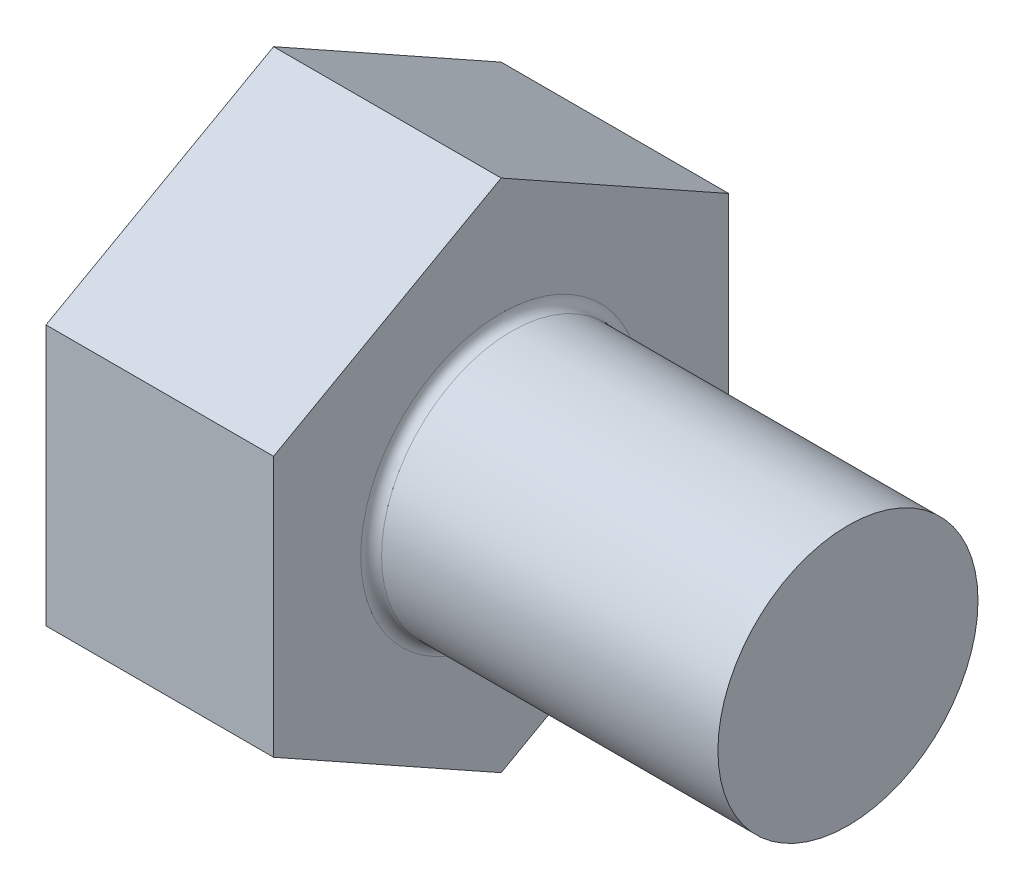
SolidWorks part; units mm, degrees
material "Brass"
ref_plane "Front Plane" through (0, 0, 0) normal (0, 0, 1) x (1, 0, 0)
ref_plane "Top Plane" through (0, 0, 0) normal (0, 1, 0) x (1, 0, 0)
ref_plane "Right Plane" through (0, 0, 0) normal (1, 0, 0) x (0, 0, -1)
sketch "Sketch1" plane through (0, 0, 0) normal (0, 0, 1) x (1, 0, 0)
  line L0 (-10.5833, 0) -> (15.2015, 0) construction
  line L2 (0, 0) -> (8.4667, 0)
  line L3 (0, 0) -> (0, 3.175)
  line L4 (0, 3.175) -> (8.4667, 3.175)
  line L5 (8.4667, 0) -> (8.4667, 3.175)
  dimension "D1" = 8.4667
  dimension "D2" = 3.175
revolve "Revolve1" add sketch "Sketch1" angle 360 about L0
sketch "Sketch2" plane through (0, 0, 0) normal (-1, 0, 0) x (0, 0, 1)
  line L0 (0, 0) -> (0, 7.3992) construction
  line L1 (0, 0) -> (0, -7.4031) construction
  line L2 (-13.4369, 0) -> (13.4369, 0) construction
  line L3 (-5.5562, 0) -> (5.5562, 0) construction
  line L4 (-5.5562, -3.1823) -> (-5.5562, 3.1823)
  line L5 (5.5562, -3.1823) -> (5.5562, 3.1823)
  line L6 (0, -6.2865) -> (0, 6.2865) construction
  line L7 (-5.5562, 3.1823) -> (0, 6.2865)
  line L8 (0, 6.2865) -> (5.5562, 3.1823)
  line L9 (5.5562, -3.1823) -> (0, -6.2865)
  line L10 (0, -6.2865) -> (-5.5562, -3.1823)
  point P7 (0, 0)
  point P10 (0, 0)
  point P12 (-5.5562, 0)
  point P16 (5.5562, 0)
  point P18 (0, 0)
  dimension "D1" = 11.1125
  dimension "D2" = 12.573
extrude "Boss-Extrude1" add sketch "Sketch2" along normal blind 5.5562
fillet "Fillet1" radius 0.254 1 edges at (0, 0, 3.175)
